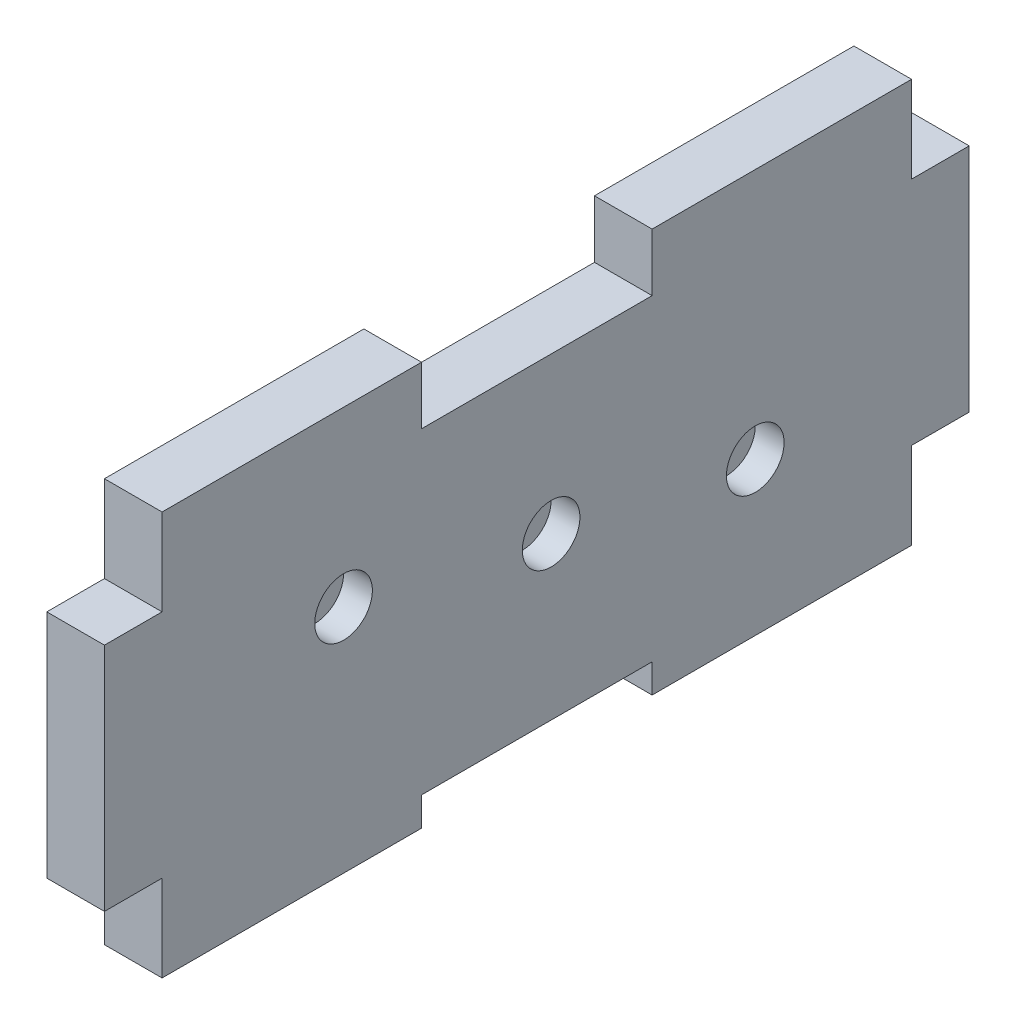
SolidWorks part; units mm, degrees
ref_plane "Front Plane" through (0, 0, 0) normal (0, 0, 1) x (1, 0, 0)
ref_plane "Top Plane" through (0, 0, 0) normal (0, 1, 0) x (1, 0, 0)
ref_plane "Right Plane" through (0, 0, 0) normal (1, 0, 0) x (0, 0, -1)
sketch "Sketch1" plane through (0, 0, 0) normal (1, 0, 0) x (0, 0, -1)
  line L1 (-150, 70) -> (0, 70)
  line L2 (-150, 70) -> (-150, 0)
  line L3 (-150, 0) -> (0, 0)
  line L4 (0, 70) -> (0, 0)
  line L5 (-150, 70) -> (-140, 70)
  line L6 (-150, 70) -> (-150, 55)
  line L7 (-150, 55) -> (-140, 55)
  line L8 (-140, 70) -> (-140, 55)
  line L9 (-150, 0) -> (-140, 0)
  line L10 (-150, 0) -> (-150, 15)
  line L11 (-150, 15) -> (-140, 15)
  line L12 (-140, 0) -> (-140, 15)
  line L13 (0, 70) -> (-10, 70)
  line L14 (0, 70) -> (0, 55)
  line L15 (0, 55) -> (-10, 55)
  line L16 (-10, 70) -> (-10, 55)
  line L17 (0, 0) -> (-10, 0)
  line L18 (0, 0) -> (0, 15)
  line L19 (0, 15) -> (-10, 15)
  line L20 (-10, 0) -> (-10, 15)
  line L21 (-95, 70) -> (-55, 70)
  line L22 (-95, 70) -> (-95, 60)
  line L23 (-95, 60) -> (-55, 60)
  line L24 (-55, 70) -> (-55, 60)
  line L25 (-95, 0) -> (-55, 0)
  line L26 (-95, 0) -> (-95, 5)
  line L27 (-95, 5) -> (-55, 5)
  line L28 (-55, 0) -> (-55, 5)
  dimension "D1" = 150
  dimension "D2" = 70
  dimension "D3" = 10
  dimension "D4" = 15
  dimension "D5" = 10
  dimension "D6" = 15
  dimension "D7" = 15
  dimension "D8" = 10
  dimension "D9" = 10
  dimension "D10" = 15
  dimension "D11" = 10
  dimension "D12" = 40
  dimension "D13" = 55
  dimension "D14" = 55
  dimension "D15" = 40
  dimension "D16" = 5
extrude "Boss-Extrude1" add sketch "Sketch1" along normal blind 5 contours L28 L3 L20 L19 L4 L15 L16 L1 L24 L23 L22 L8 L7 L2 L11 L12 L26 L27
sketch "Sketch2" plane through (5, 0, 0) normal (1, 0, 0) x (0, 0, -1)
  line L1 (-150, 55) -> (-150, 15) construction
  line L2 (-95, 5) -> (-55, 5) construction
  circle A0 centre (-108.52, 40) radius 5
  dimension "D3" = 10
  dimension "D1" = 35
  dimension "D2" = 41.48
sketch "Sketch5" plane through (0, 0, 0) normal (-1, 0, 0) x (0, 0, 1)
  line L0 (95, 5) -> (55, 5) construction
  line L1 (55, 5) -> (10, 5)
  line L2 (10, 0) -> (10, 15) construction
  line L3 (140, 70) -> (140, 55) construction
  circle A0 centre (72.52, 33) radius 5
  circle A1 centre (37.1117, 26.5) radius 5
  dimension "D1" = 10
  dimension "D4" = 10
  dimension "D6" = 21.5
  dimension "D2" = 28
  dimension "D3" = 67.48
  dimension "D5" = 36
extrude "Cut-Extrude4" cut sketch "Sketch5" against normal blind 5 contours A1 | A0
extrude "Cut-Extrude5" cut sketch "Sketch2" against normal blind 5
sketch "Sketch6" plane through (0, 0, 0) normal (-1, 0, 0) x (0, 0, 1)
  line L40 (55, 0) -> (55, 5)
  line L41 (55, 5) -> (95, 5)
  line L42 (95, 5) -> (95, 0)
  line L43 (95, 0) -> (140, 0)
  line L44 (140, 0) -> (140, 15)
  line L45 (140, 15) -> (150, 15)
  line L46 (150, 15) -> (150, 55)
  line L47 (150, 55) -> (140, 55)
  line L48 (140, 55) -> (140, 70)
  line L49 (140, 70) -> (95, 70)
  line L50 (95, 70) -> (95, 60)
  line L51 (95, 60) -> (55, 60)
  line L52 (55, 60) -> (55, 70)
  line L53 (55, 70) -> (10, 70)
  line L54 (10, 70) -> (10, 55)
  line L55 (10, 55) -> (0, 55)
  line L56 (0, 55) -> (0, 15)
  line L57 (0, 15) -> (10, 15)
  line L58 (10, 15) -> (10, 0)
  line L59 (10, 0) -> (55, 0)
  line L60 (55, 0) -> (55, 5)
  line L61 (55, 5) -> (95, 5)
  line L62 (95, 5) -> (95, 0)
  line L63 (95, 0) -> (140, 0)
  line L64 (140, 0) -> (140, 15)
  line L65 (140, 15) -> (150, 15)
  line L66 (150, 15) -> (150, 55)
  line L67 (150, 55) -> (140, 55)
  line L68 (140, 55) -> (140, 70)
  line L69 (140, 70) -> (95, 70)
  line L70 (95, 70) -> (95, 60)
  line L71 (95, 60) -> (55, 60)
  line L72 (55, 60) -> (55, 70)
  line L73 (55, 70) -> (10, 70)
  line L74 (10, 70) -> (10, 55)
  line L75 (10, 55) -> (0, 55)
  line L76 (0, 55) -> (0, 15)
  line L77 (0, 15) -> (10, 15)
  line L78 (10, 15) -> (10, 0)
  line L79 (10, 0) -> (55, 0)
  dimension "D1" = 0
extrude "Boss-Extrude2" add sketch "Sketch6" along normal blind 5
